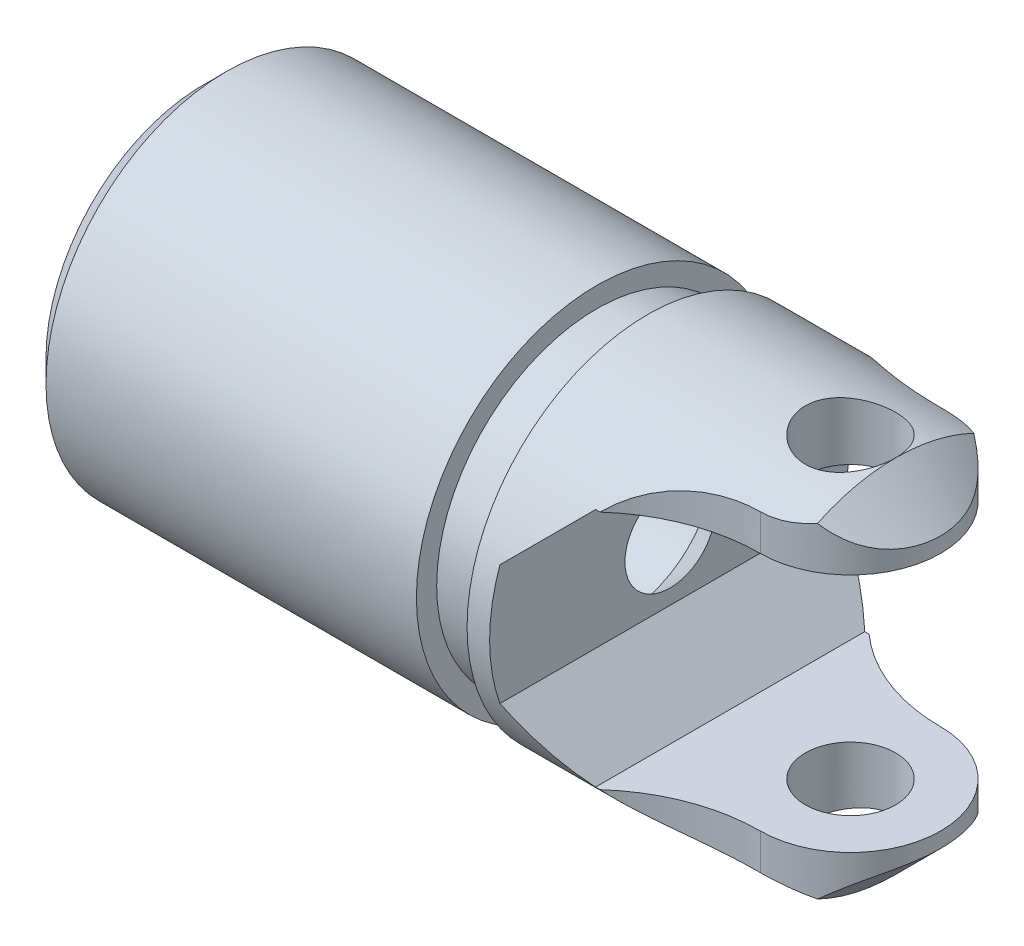
SolidWorks part; units mm, degrees
ref_plane "Front Plane" through (0, 0, 0) normal (0, 0, 1) x (1, 0, 0)
ref_plane "Top Plane" through (0, 0, 0) normal (0, 1, 0) x (1, 0, 0)
ref_plane "Right Plane" through (0, 0, 0) normal (1, 0, 0) x (0, 0, -1)
sketch "Sketch0" plane through (0, 0, 0) normal (0, 1, 0) x (1, 0, 0)
  line L0 (-34.1313, 0) -> (34.1313, 0) construction
  line L1 (-34.1313, 9.525) -> (-34.1313, -9.525) construction
  line L2 (-11.9063, 4.7625) -> (-11.9063, -4.7625) construction
  line L3 (-11.9063, 4.7625) -> (-7.1438, 0) construction
  line L4 (-7.1438, 0) -> (-11.9063, -4.7625) construction
  line L5 (-9.525, 2.3812) -> (-9.525, -2.3812) construction
  point P7 (-11.9063, 0)
  point P8 (0, 0)
  point P12 (-9.525, 0)
sketch "Sketch1" plane through (0, 0, 0) normal (0, 1, 0) x (1, 0, 0)
  line L0 (-34.1313, 9.525) -> (-13.3896, 9.525)
  line L1 (4.7625, 9.525) -> (4.7625, 0)
  line L2 (4.7625, 0) -> (-34.1313, 0)
  line L3 (-34.1313, 0) -> (-34.1313, 9.525)
  line L4 (-34.1313, 9.525) -> (-34.1313, -9.525) construction
  line L5 (-34.1313, 0) -> (34.1313, 0) construction
  line L6 (-10.7156, 9.525) -> (4.7625, 9.525)
  line L7 (-10.7156, 2.3812) -> (-10.7156, 8.4554) construction
  line L8 (-13.3896, 9.525) -> (-13.3896, 8.4554)
  line L9 (-13.3896, 8.4554) -> (-10.7156, 8.4554)
  line L10 (-10.7156, 9.525) -> (-10.7156, 8.4554)
  line L11 (0, 0) -> (9.525, 0) construction
  line L12 (-9.525, 2.3812) -> (-11.9063, 2.3812) construction
  line L13 (-11.9063, 4.7625) -> (-11.9063, -4.7625) construction
  circle A0 centre (0, 0) radius 9.525 construction
  dimension "D1" = 2.6739
  dimension "D2" = 1.0696
  dimension "D3" = 38.8937
revolve "Revolve1" add sketch "Sketch1" angle 360 about L0
chamfer "Chamfer1" distance 1.1906 angle 45 1 edges at (-34.1313, 0, 9.525)
chamfer "Chamfer2" distance 2.3813 angle 45 1 edges at (4.7625, 0, 9.525)
sketch "Sketch2" plane through (0, 0, 0) normal (0, 1, 0) x (1, 0, 0)
  line L0 (-10.7156, 9.525) -> (-8.0417, 9.525) construction
  line L1 (-10.7156, 9.525) -> (4.7625, 9.525) construction
  line L2 (2.3813, 9.525) -> (-10.7156, 9.525) construction
  line L3 (-13.3896, 8.4554) -> (-10.7156, 8.4554) construction
  line L4 (-34.1313, 0) -> (4.7625, 0) construction
  line L5 (-8.0417, 9.525) -> (9.525, 9.525)
  line L6 (9.525, 9.525) -> (9.525, -9.525)
  line L7 (9.525, -9.525) -> (-8.0417, -9.525)
  line L8 (0, 4.7625) -> (0, 0) construction
  arc A0 (-8.0417, 9.525) -> (0, 4.7625) centre (0, 13.9331) ccw
  arc A1 (0, -4.7625) -> (0, 4.7625) centre (0, 0) ccw
  arc A2 (-8.0417, -9.525) -> (0, -4.7625) centre (0, -13.9331) cw
  dimension "D1" = 9.525
extrude "Extrude1" cut sketch "Sketch2" against normal through all and the other way through all
sketch "Sketch3" plane through (0, 0, 0) normal (0, 0, 1) x (1, 0, 0)
  line L0 (-6.3532, 6.3436) -> (-9.525, 3.1718)
  line L1 (-6.3532, 6.3436) -> (9.525, 6.3437)
  line L2 (-9.525, 3.1718) -> (-9.525, -3.1718)
  line L3 (-6.3532, -6.3436) -> (9.525, -6.3437)
  line L4 (9.525, 6.3437) -> (9.525, -6.3437)
  line L5 (-9.525, -3.1718) -> (-6.3532, -6.3436)
  dimension "D1" = 12.6873
  dimension "D2" = 3.1718
extrude "Extrude3" cut sketch "Sketch3" against normal through all and the other way through all
sketch "Sketch4" plane through (-34.1313, 0, 0) normal (-1, 0, 0) x (0, 0, 1)
  circle A0 centre (0, 0) radius 4.7625
extrude "Extrude4" cut sketch "Sketch4" against normal up to vertex (22.225 mm away) up to point (-11.9063, 0, -4.7625)
sketch "Sketch5" plane through (-11.9063, 0, 0) normal (-1, 0, 0) x (0, 0, 1)
  circle A0 centre (0, 0) radius 4.7625 construction
  circle A1 centre (0, 0) radius 4.7625
extrude "Extrude5" cut sketch "Sketch5" against normal through all draft 45
sketch "Sketch6" plane through (0, 0, 0) normal (0, 1, 0) x (1, 0, 0)
  line L0 (-34.1313, 0) -> (34.1313, 0) construction
  line L1 (4.7625, 0) -> (2.3812, 0) construction
  line L2 (2.3812, 0) -> (0, 0) construction
  circle A0 centre (0, 0) radius 2.3812
  arc A1 (0, -4.7625) -> (0, 4.7625) centre (0, 0) ccw construction
  dimension "D1" = 4.7625
extrude "Extrude6" cut sketch "Sketch6" against normal through all and the other way through all
equation "\"D2@Sketch3\" = \"D1@Sketch3\" / 4"
equation "\"D1@Extrude14\" = \"OD@Sketch0\""
equation "\"D1@Extrude16\" = \"D1@Extrude14\""
equation "\"D1@Sketch3\" = \"OD@Sketch0\"*.666"
equation "\"D2@Sketch3\" = \"D1@Sketch3\"/4"
equation "\"D1@Sketch1\" = \"D3@Sketch1\"*.06875"
equation "\"D2@Sketch1\" = \"D1@Sketch1\"/2.5"
equation "\"D1@Chamfer1\" = \"OD@Sketch0\"/16"
equation "\"D1@Chamfer2\" = \"D1@Chamfer1\"*2"
equation "\"D1@Chamfer3\" = \"D1@Chamfer1\"*.50"
